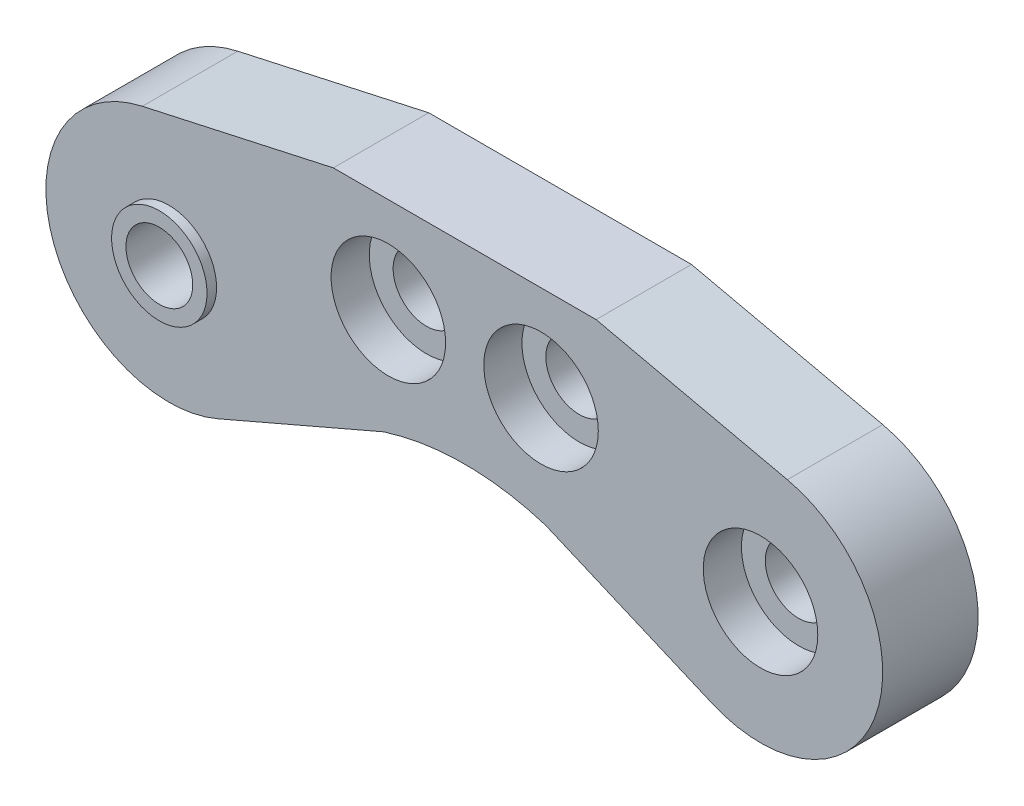
SolidWorks part; units mm, degrees
material "ABS"
ref_plane "Front Plane" through (0, 0, 0) normal (0, 0, 1) x (1, 0, 0)
ref_plane "Top Plane" through (0, 0, 0) normal (0, 1, 0) x (1, 0, 0)
ref_plane "Right Plane" through (0, 0, 0) normal (1, 0, 0) x (0, 0, -1)
sketch "Sketch1" plane through (0, 0, 0) normal (0, 0, 1) x (1, 0, 0)
  line L0 (23.1168, 8) -> (36.8832, 8)
  line L1 (25.7556, -2.6589) -> (17.0541, -6.4157)
  line L2 (34.2444, -2.6589) -> (42.9891, -6.388)
  line L3 (13.1115, 5.7922) -> (23.1168, 8)
  line L4 (46.9052, 5.7448) -> (36.8832, 8)
  arc A0 (13.1115, 5.7922) -> (17.0541, -6.4157) centre (14.5, -0.5) ccw
  arc A1 (42.9891, -6.388) -> (46.9052, 5.7448) centre (45.5, -0.5) ccw
  arc A2 (34.2444, -2.6589) -> (25.7556, -2.6589) centre (30, -16) ccw
extrude "Boss-Extrude1" add sketch "Sketch1" along normal blind 5
sketch "Sketch2" plane through (0, 0, 5) normal (0, 0, 1) x (1, 0, 0)
  circle A1 centre (45.5, -0.5) radius 1.75
  circle A2 centre (14.5, -0.5) radius 1.75
  circle A3 centre (26, 3) radius 1.75
  circle A4 centre (34, 3) radius 1.75
  dimension "D4" = 3.5
  dimension "D1" = 11.5
  dimension "D2" = 8
  dimension "D3" = 3.5
extrude "Cut-Extrude1" cut sketch "Sketch2" against normal through all both and the other way through all
sketch "Sketch3" plane through (0, 0, 5) normal (0, 0, 1) x (1, 0, 0)
  circle A0 centre (14.5, -0.5) radius 1.75
  circle A1 centre (14.5, -0.5) radius 2.5
  dimension "D1" = 5
extrude "Boss-Extrude2" add sketch "Sketch3" along normal blind 0.5
sketch "Sketch5" plane through (0, 0, 5) normal (0, 0, 1) x (1, 0, 0)
  circle A0 centre (26, 3) radius 3
  circle A1 centre (34, 3) radius 3
  circle A2 centre (45.5, -0.5) radius 3
  dimension "D1" = 6
extrude "Cut-Extrude2" cut sketch "Sketch5" against normal blind 2
equation "\"D1@Sketch2\"=(31-8)/2"
